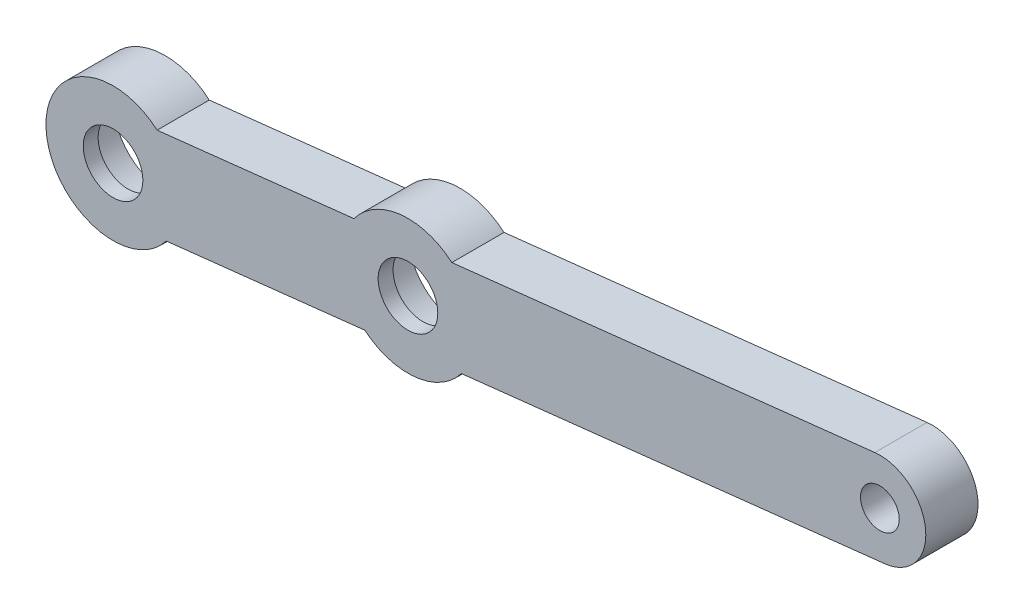
SolidWorks part; units mm, degrees
ref_plane "Front Plane" through (0, 0, 0) normal (0, 0, 1) x (1, 0, 0)
ref_plane "Top Plane" through (0, 0, 0) normal (0, 1, 0) x (1, 0, 0)
ref_plane "Right Plane" through (0, 0, 0) normal (1, 0, 0) x (0, 0, -1)
sketch "Sketch1" plane through (0, 0, 0) normal (0, 0, 1) x (1, 0, 0)
  line L2 (-117.8424, -77.0683) -> (-91.2212, -74.1121)
  line L3 (-92.666, -61.8727) -> (-119.0791, -64.8059)
  line L4 (-22.8116, -54.1154) -> (-79.5428, -60.4154)
  line L6 (-78.2671, -72.6736) -> (-21.4514, -66.3642)
  circle A3 centre (-22.1315, -60.2398) radius 2.6
  circle A4 centre (-85.4292, -67.2234) radius 6.9
  arc A5 (-91.2212, -74.1121) -> (-78.2671, -72.6736) centre (-85.4292, -67.2234) ccw
  arc A6 (-21.4514, -66.3642) -> (-22.8116, -54.1154) centre (-22.1315, -60.2398) ccw
  arc A9 (-79.5428, -60.4154) -> (-92.666, -61.8727) centre (-85.4292, -67.2234) ccw
  circle A10 centre (-124.987, -71.5953) radius 6.9
  arc A11 (-119.0791, -64.8059) -> (-117.8424, -77.0683) centre (-124.987, -71.5953) ccw
extrude "Boss-Extrude1" add sketch "Sketch1" along normal blind 5
sketch "Sketch2" plane through (0, 0, 5) normal (0, 0, 1) x (1, 0, 0)
  line L4 (-22.8116, -54.1154) -> (-79.5428, -60.4154)
  line L5 (-92.666, -61.8727) -> (-119.0791, -64.8059)
  line L6 (-117.8424, -77.0683) -> (-91.2212, -74.1121)
  line L7 (-78.2671, -72.6736) -> (-21.4514, -66.3642)
  line L8 (-22.8116, -54.1154) -> (-79.5428, -60.4154)
  line L9 (-92.666, -61.8727) -> (-119.0791, -64.8059)
  line L10 (-117.8424, -77.0683) -> (-91.2212, -74.1121)
  line L11 (-78.2671, -72.6736) -> (-21.4514, -66.3642)
  circle A0 centre (-22.1315, -60.2398) radius 2.6
  circle A1 centre (-85.4292, -67.2234) radius 4
  circle A2 centre (-124.987, -71.5953) radius 4
  arc A4 (-21.4514, -66.3642) -> (-22.8116, -54.1154) centre (-22.1315, -60.2398) ccw
  arc A5 (-79.5428, -60.4154) -> (-92.666, -61.8727) centre (-85.4292, -67.2234) ccw
  arc A6 (-119.0791, -64.8059) -> (-117.8424, -77.0683) centre (-124.987, -71.5953) ccw
  arc A7 (-91.2212, -74.1121) -> (-78.2671, -72.6736) centre (-85.4292, -67.2234) ccw
  arc A8 (-21.4514, -66.3642) -> (-22.8116, -54.1154) centre (-22.1315, -60.2398) ccw
  arc A9 (-79.5428, -60.4154) -> (-92.666, -61.8727) centre (-85.4292, -67.2234) ccw
  arc A10 (-119.0791, -64.8059) -> (-117.8424, -77.0683) centre (-124.987, -71.5953) ccw
  arc A11 (-91.2212, -74.1121) -> (-78.2671, -72.6736) centre (-85.4292, -67.2234) ccw
  dimension "D2" = 5.2
  dimension "D3" = 8
  dimension "D4" = 8
  dimension "D1" = 0
extrude "Boss-Extrude2" add sketch "Sketch2" along normal blind 2
